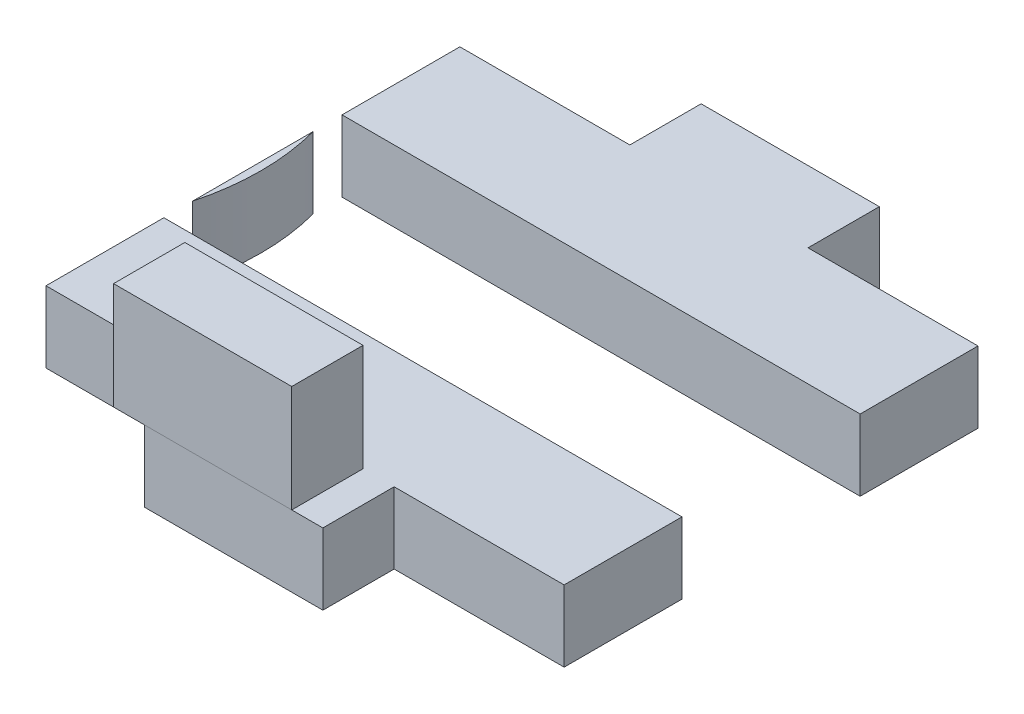
SolidWorks part; units mm, degrees
ref_plane "Front Plane" through (0, 0, 0) normal (0, 0, 1) x (1, 0, 0)
ref_plane "Top Plane" through (0, 0, 0) normal (0, 1, 0) x (1, 0, 0)
ref_plane "Right Plane" through (0, 0, 0) normal (1, 0, 0) x (0, 0, -1)
sketch "Sketch1" plane through (0, 0, 0) normal (0, 1, 0) x (1, 0, 0)
  line L0 (36.7869, 11.6138) -> (41.7869, 11.6138)
  line L1 (27.5186, 11.6138) -> (12.7082, 11.6138)
  line L2 (27.5186, -11.6138) -> (12.7082, -11.6138)
  line L3 (0, 0) -> (46.96, 0) construction
  line L4 (36.7869, -11.6138) -> (41.7869, -11.6138)
  line L5 (41.7869, 11.6138) -> (41.7869, -11.6138)
  line L10 (27.5186, 11.6138) -> (36.7869, 11.6138)
  line L11 (12.7082, 11.6138) -> (12.7082, -11.6138)
  line L15 (27.5186, -11.6138) -> (36.7869, -11.6138)
  circle A15 centre (16.5, 0) radius 2.5
  circle A16 centre (22.5, 0) radius 2.5
  circle A17 centre (28.5, 0) radius 2.5
  circle A18 centre (34.5, 0) radius 2.5
extrude "Boss-Extrude2" add sketch "Sketch1" along normal blind 4
sketch "Sketch12" plane through (0, 0, -11.6138) normal (0, 0, -1) x (-1, 0, 0)
  line L3 (-41.7869, 4) -> (-12.7082, 4) construction
  line L4 (-32.2475, 0) -> (-22.2475, 0)
  line L5 (-32.2475, 0) -> (-32.2475, 4)
  line L6 (-32.2475, 4) -> (-22.2475, 4)
  line L7 (-22.2475, 0) -> (-22.2475, 4)
  point P6 (-27.2475, 2)
  dimension "D1" = 10
extrude "Boss-Extrude4" add sketch "Sketch12" along normal blind 4
sketch "Sketch13" plane through (0, 4, 0) normal (0, 1, 0) x (1, 0, 0)
  line L0 (16.5, 0) -> (34.5, 0) construction
sketch "Sketch14" plane through (0, 0, 11.6138) normal (0, 0, 1) x (1, 0, 0)
  line L0 (12.7082, 2) -> (41.7869, 2) construction
  line L1 (12.7082, 4) -> (12.7082, 0) construction
  line L2 (41.7869, 4) -> (41.7869, 0) construction
  line L3 (12.7082, 4) -> (41.7869, 4) construction
  line L4 (22.2475, 0) -> (32.2475, 0)
  line L5 (22.2475, 0) -> (22.2475, 4)
  line L6 (22.2475, 4) -> (32.2475, 4)
  line L7 (32.2475, 0) -> (32.2475, 4)
  line L8 (22.2475, 0) -> (32.2475, 4) construction
  line L9 (22.2475, 4) -> (32.2475, 0) construction
  point P6 (27.2475, 2)
  dimension "D1" = 10
extrude "Boss-Extrude5" add sketch "Sketch14" along normal blind 4
sketch "Sketch5" plane through (0, 0, 0) normal (0, -1, 0) x (1, 0, 0)
  line L0 (16.5, 0) -> (34.5, 0)
  circle A3 centre (16.5, 0) radius 2.5
  circle A4 centre (22.5, 0) radius 2.5
  circle A5 centre (28.5, 0) radius 2.5
  circle A6 centre (34.5, 0) radius 2.5
  dimension "D2" = 4
sketch "Sketch10" plane through (0, 4, 0) normal (0, 1, 0) x (1, 0, 0)
  line L1 (41.8123, 5) -> (41.8123, -5)
  line L2 (12.1636, -5) -> (41.8123, -5)
  line L3 (12.1636, 5) -> (41.8123, 5)
  arc A0 (12.1636, 5) -> (12.1636, -5) centre (0, 0) cw
  arc A1 (9.068, -9.525) -> (9.068, 9.525) centre (0, 0) ccw construction
extrude "Cut-Extrude1" cut sketch "Sketch10" against normal blind 6
sketch "Sketch11" plane through (0, 0, 11.6138) normal (0, 0, 1) x (1, 0, 0)
  line L1 (12.1636, 4) -> (41.7869, 4) construction
  line L2 (20.5, 10) -> (30.5, 10)
  line L3 (20.5, 10) -> (20.5, 4)
  line L4 (20.5, 4) -> (30.5, 4)
  line L6 (30.5, 10) -> (30.5, 4)
  line L7 (20.5, 10) -> (30.5, 4) construction
  line L8 (20.5, 4) -> (30.5, 10) construction
extrude "Boss-Extrude3" add sketch "Sketch11" along normal blind 4
